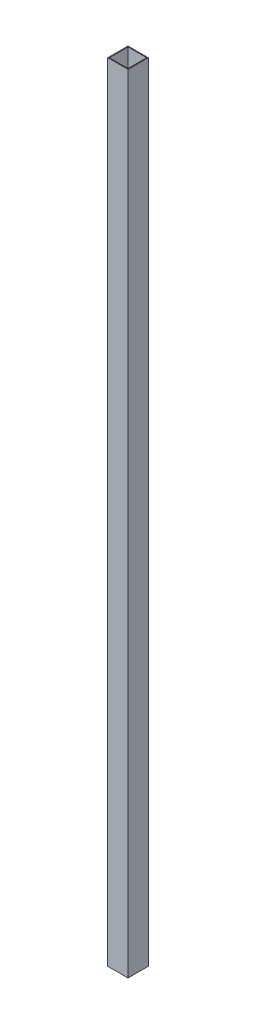
SolidWorks part; units mm, degrees
ref_plane "Front Plane" through (0, 0, 0) normal (0, 0, 1) x (1, 0, 0)
ref_plane "Top Plane" through (0, 0, 0) normal (0, 1, 0) x (1, 0, 0)
ref_plane "Right Plane" through (0, 0, 0) normal (1, 0, 0) x (0, 0, -1)
sketch "Sketch1" plane through (0, 0, 0) normal (0, 1, 0) x (1, 0, 0)
  line L0 (-11.5, 11.5) -> (11.5, 11.5)
  line L1 (-12.5, -12.5) -> (12.5, -12.5)
  line L2 (-12.5, -12.5) -> (-12.5, 12.5)
  line L3 (-12.5, 12.5) -> (12.5, 12.5)
  line L4 (12.5, -12.5) -> (12.5, 12.5)
  line L5 (-12.5, -12.5) -> (12.5, 12.5) construction
  line L6 (-12.5, 12.5) -> (12.5, -12.5) construction
  line L7 (11.5, -11.5) -> (11.5, 11.5)
  line L8 (-11.5, -11.5) -> (11.5, -11.5)
  line L9 (-11.5, -11.5) -> (-11.5, 11.5)
  point P0 (0, 0)
  dimension "D2" = 25
  dimension "D3" = 25
  dimension "D1" = 1
extrude "Boss-Extrude1" add sketch "Sketch1" along normal blind 971
